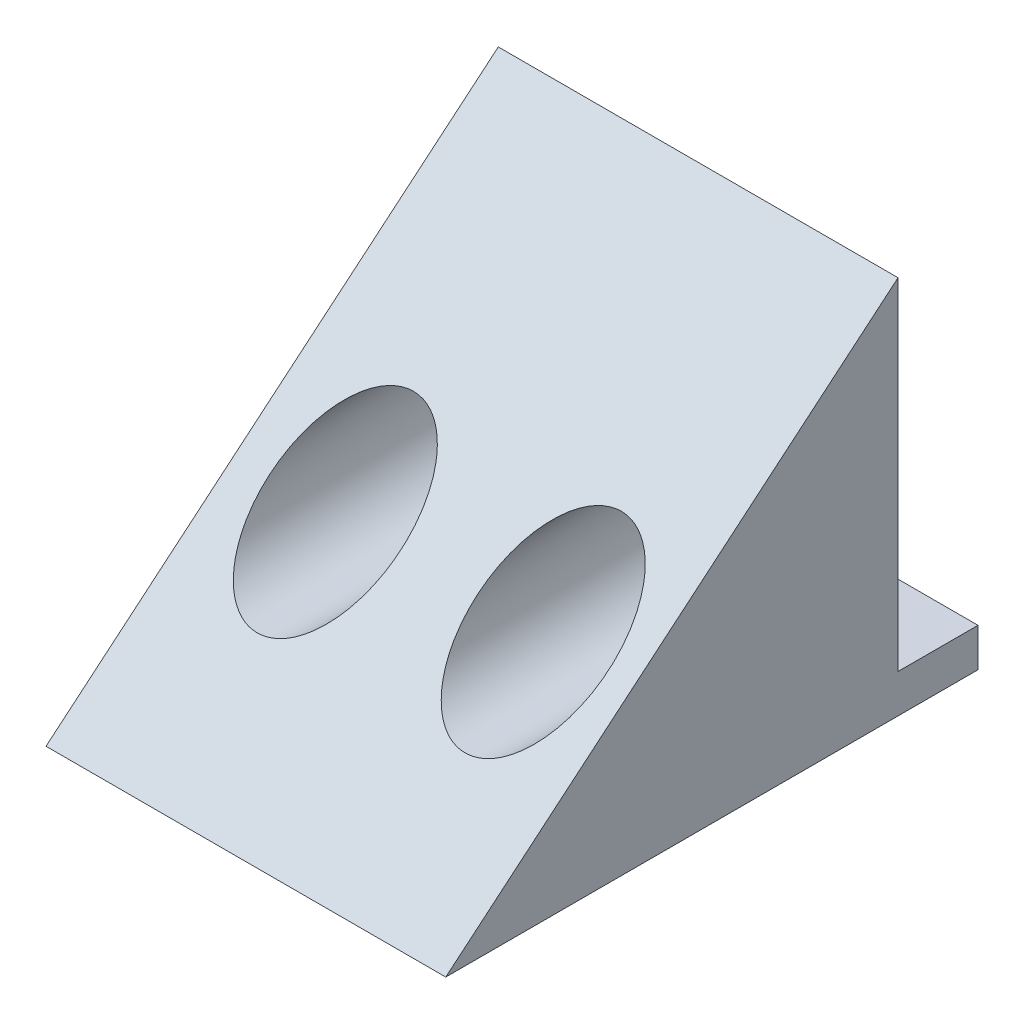
SolidWorks part; units mm, degrees
ref_plane "Alzado" through (0, 0, 0) normal (0, 0, 1) x (1, 0, 0)
ref_plane "Planta" through (0, 0, 0) normal (0, 1, 0) x (1, 0, 0)
ref_plane "Vista lateral" through (0, 0, 0) normal (1, 0, 0) x (0, 0, -1)
sketch "Sketch1" plane through (0, 0, 0) normal (1, 0, 0) x (0, 0, -1)
  line L0 (0, 0) -> (56.5672, 0)
  line L1 (0, 0) -> (56.5672, 47.4655)
  line L2 (56.5672, 0) -> (56.5672, 47.4655)
  point P4 (56.5672, 48.5368)
  dimension "D1" = 140
extrude "Boss-Extrude1" add sketch "Sketch1" along normal blind 50
sketch "Sketch6" plane through (0, 0, -56.5672) normal (0, 0, -1) x (-1, 0, 0)
  line L0 (-50, 0) -> (0, 0) construction
  circle A0 centre (-38.5544, 19.83) radius 8.2
  circle A1 centre (-12.5544, 19.83) radius 8.2
  point P6 (-12.5544, 19.83)
  point P8 (-49.0291, 36.0216)
  dimension "D2" = 16.4
  dimension "D3" = 16.4
  dimension "D1" = 19.83
  dimension "D4" = 26
  dimension "D5" = 19.83
extrude "Cut-Extrude5" cut sketch "Sketch6" against normal blind 75.17
sketch "Sketch7" plane through (0, 0, -56.5672) normal (0, 0, -1) x (-1, 0, 0)
  line L1 (-50, 0) -> (0, 0)
  line L2 (-50, 0) -> (-50, 4.8187)
  line L3 (-50, 4.8187) -> (0, 4.8187)
  line L4 (0, 0) -> (0, 4.8187)
  line L5 (-50, 0) -> (0, 4.8187) construction
  line L6 (-50, 4.8187) -> (0, 0) construction
  point P4 (-25, 2.4093)
extrude "Boss-Extrude3" add sketch "Sketch7" along normal blind 10
sketch "Sketch8" plane through (0, 4.8187, 0) normal (0, 1, 0) x (1, 0, 0)
  circle A0 centre (24.6819, 61.8784) radius 1.585
  dimension "D1" = 3.17
extrude "Cut-Extrude6" cut sketch "Sketch8" against normal blind 10
